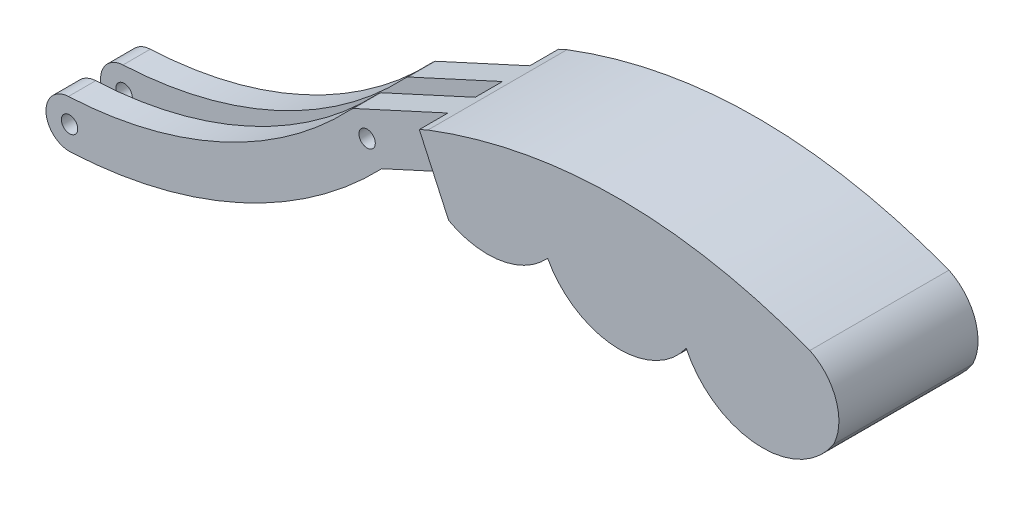
SolidWorks part; units mm, degrees
ref_plane "Alzado" through (0, 0, 0) normal (0, 0, 1) x (1, 0, 0)
ref_plane "Planta" through (0, 0, 0) normal (0, 1, 0) x (1, 0, 0)
ref_plane "Vista lateral" through (0, 0, 0) normal (1, 0, 0) x (0, 0, -1)
sketch "Croquis1" plane through (0, 0, 0) normal (0, 0, 1) x (1, 0, 0)
  line L0 (0, 0) -> (109.0871, 50) construction
  line L1 (0, 0) -> (109.0871, 0) construction
  line L2 (0, 0) -> (0, 50) construction
  line L3 (0, 50) -> (109.0871, 50) construction
  line L4 (109.0871, 0) -> (109.0871, 50) construction
  line L5 (-3.5418, 7.7272) -> (105.5454, 57.7272)
  line L6 (3.5418, -7.7272) -> (112.6289, 42.2728)
  line L7 (105.5454, 57.7272) -> (141.9077, 74.3939)
  line L8 (141.9077, 74.3939) -> (281.9077, 74.3939) construction
  line L9 (137.5866, 44.3939) -> (295.5187, 44.3939) construction
  line L10 (112.6289, 42.2728) -> (141.6607, 55.5795)
  line L11 (-115.9332, 146.9064) -> (496.581, 7.0587) construction
  line L12 (-126.393, 122.6183) -> (-105.4734, 171.1945) construction
  circle A0 centre (0, 0) radius 3
  circle A1 centre (109.0871, 50) radius 3
  arc A2 (-3.5418, 7.7272) -> (3.5418, -7.7272) centre (0, 0) ccw
  arc A3 (112.6289, 42.2728) -> (105.5454, 57.7272) centre (109.0871, 50) ccw
  arc A4 (141.6607, 55.5795) -> (185.7693, 55.5795) centre (163.715, 75.6745) ccw
  arc A5 (185.7693, 55.5795) -> (236.5692, 52.4119) centre (212.1557, 69.8157) ccw
  arc A6 (236.5692, 52.4119) -> (290.5982, 48.9261) centre (264.5615, 65.8243) ccw
  arc A7 (0, 0) -> (109.0871, 50) centre (-7.5149, 160.3955) ccw construction
  arc A8 (290.5982, 48.9261) -> (281.9077, 74.3939) centre (273.5191, 57.3148) ccw
  arc A9 (0.4045, -8.6326) -> (115.3627, 44.0584) centre (-7.5149, 160.3955) ccw
  arc A10 (-0.4045, 8.6326) -> (102.8115, 55.9416) centre (-7.5149, 160.3955) ccw
  arc A11 (-0.4045, 8.6326) -> (0.4045, -8.6326) centre (0, 0) ccw
  arc A12 (115.3627, 44.0584) -> (102.8115, 55.9416) centre (109.0871, 50) ccw
  spline S0 degree 2 poles (141.9077, 74.3939) (211.7052, 100.8392) (281.9077, 74.3939) knots 0 0 0 1 1 1
  point P7 (54.5436, 25)
  point P20 (185.7693, 55.5795)
  point P21 (236.5692, 52.4119)
  point P36 (59.3899, 14.4265)
  dimension "D3" = 6
  dimension "D4" = 6
  dimension "D1" = 120
  dimension "D2" = 50
  dimension "D5" = 40
  dimension "D6" = 140
  dimension "D7" = 30
extrude "Saliente-Extruir1" add sketch "Croquis1" along normal blind 51 contours S0 L7 A12 A9 L10 A4 A5 A6 A8 | A9 A12 L7 A3 L10 | L5 A12 A10 A11 A2 L6 A3 A0 A1 | L5 A11 A9 L10 L6 A2
sketch "Croquis2" plane through (-3.5418, 7.7272, 0) normal (-0.4167, 0.9091, 0) x (0.9091, 0.4167, 0)
  line L1 (-173.5002, -10.5) -> (156.4998, -10.5) construction
  line L2 (-173.5002, -10.5) -> (-173.5002, -40.5) construction
  line L3 (-173.5002, -40.5) -> (156.4998, -40.5) construction
  line L4 (156.4998, -10.5) -> (156.4998, -40.5) construction
  line L5 (-173.5002, -10.5) -> (156.4998, -40.5) construction
  line L6 (-173.5002, -40.5) -> (156.4998, -10.5) construction
  line L8 (156.4998, -10.5) -> (-25.4648, -10.5)
  line L9 (156.4998, -10.5) -> (156.4998, 17.4055)
  line L10 (156.4998, 17.4055) -> (-25.4648, 17.4055)
  line L11 (-25.4648, -10.5) -> (-25.4648, 17.4055)
  line L12 (156.4998, -40.5) -> (-18.3785, -40.5)
  line L13 (156.4998, -40.5) -> (156.4998, -100.8476)
  line L14 (156.4998, -100.8476) -> (-18.3785, -100.8476)
  line L15 (-18.3785, -40.5) -> (-18.3785, -100.8476)
  line L16 (-173.5002, -20.5) -> (156.4998, -20.5)
  line L17 (-173.5002, -20.5) -> (-173.5002, -30.5)
  line L18 (-173.5002, -30.5) -> (156.4998, -30.5)
  line L19 (156.4998, -20.5) -> (156.4998, -30.5)
  line L20 (-173.5002, -20.5) -> (156.4998, -30.5) construction
  line L21 (-173.5002, -30.5) -> (156.4998, -20.5) construction
  point P0 (-8.5002, -25.5)
  point P13 (-8.5002, -25.5)
  dimension "D1" = 30
  dimension "D2" = 330
  dimension "D3" = 10
extrude "Cortar-Extruir1" cut sketch "Croquis2" against normal through all both and the other way through all
